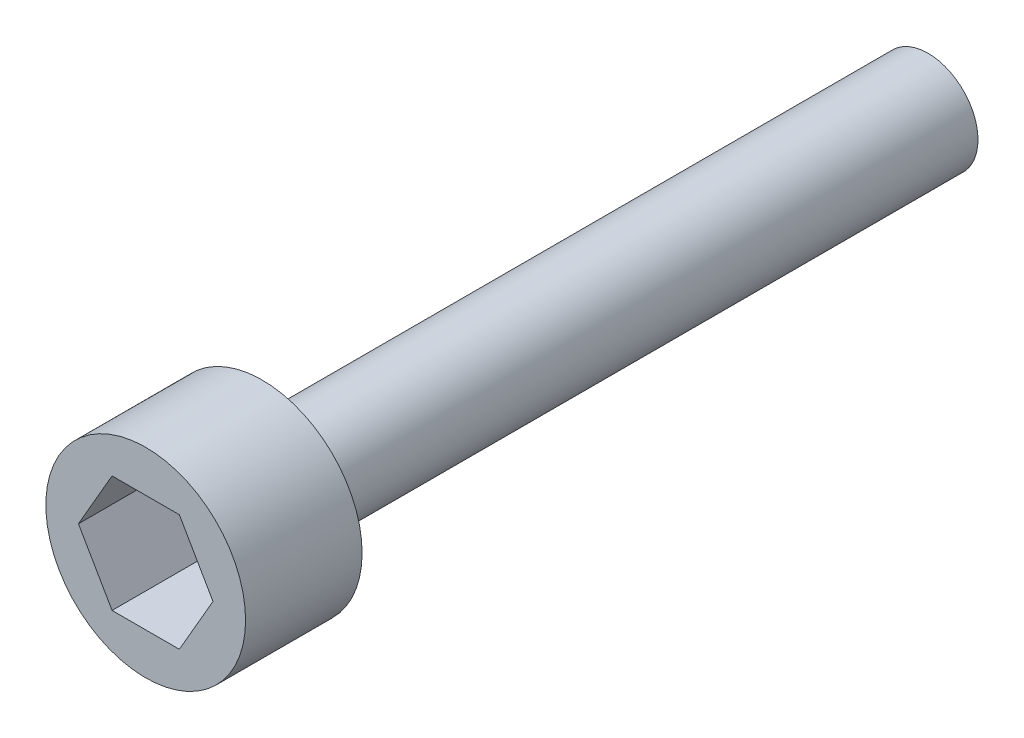
SolidWorks part; units mm, degrees
material "Alloy Steel"
ref_plane "Front Plane" through (0, 0, 0) normal (0, 0, 1) x (1, 0, 0)
ref_plane "Top Plane" through (0, 0, 0) normal (0, 1, 0) x (1, 0, 0)
ref_plane "Right Plane" through (0, 0, 0) normal (1, 0, 0) x (0, 0, -1)
sketch "Sketch1" plane through (0, 0, 0) normal (0, 0, 1) x (1, 0, 0)
  circle A0 centre (0, 0) radius 3
  dimension "D1" = 6
extrude "Head Boss-Extrude1" add sketch "Sketch1" along normal blind 3.5
sketch "Sketch3" plane through (0, 0, 3.5) normal (0, 0, 1) x (1, 0, 0)
  line L0 (-1.0104, 1.75) -> (1.0104, 1.75)
  line L1 (1.0104, 1.75) -> (2.0207, 0)
  line L2 (2.0207, 0) -> (1.0104, -1.75)
  line L3 (1.0104, -1.75) -> (-1.0104, -1.75)
  line L4 (-1.0104, -1.75) -> (-2.0207, 0)
  line L5 (-2.0207, 0) -> (-1.0104, 1.75)
  line L6 (-2.0207, 0) -> (0, 0) construction
  line L7 (2.0207, 0) -> (0, 0) construction
  line L8 (-1.0104, -1.75) -> (0, 0) construction
  line L9 (0, 0) -> (1.0104, 1.75) construction
  line L10 (-1.0104, 1.75) -> (0, 0) construction
  line L11 (0, 0) -> (1.0104, -1.75) construction
  dimension "D1" = 60
  dimension "D2" = 60
  dimension "D3" = 60
  dimension "D4" = 60
  dimension "D5" = 60
  dimension "D6" = 3.5
extrude "Head Hex Cut-Extrude1" cut sketch "Sketch3" against normal blind 2.8
sketch "Sketch2" plane through (0, 0, 0) normal (0, 0, 1) x (1, 0, 0)
  circle A0 centre (0, 0) radius 1.5
  dimension "D1" = 3
extrude "Screw Boss-Extrude2" add sketch "Sketch2" against normal blind 20
